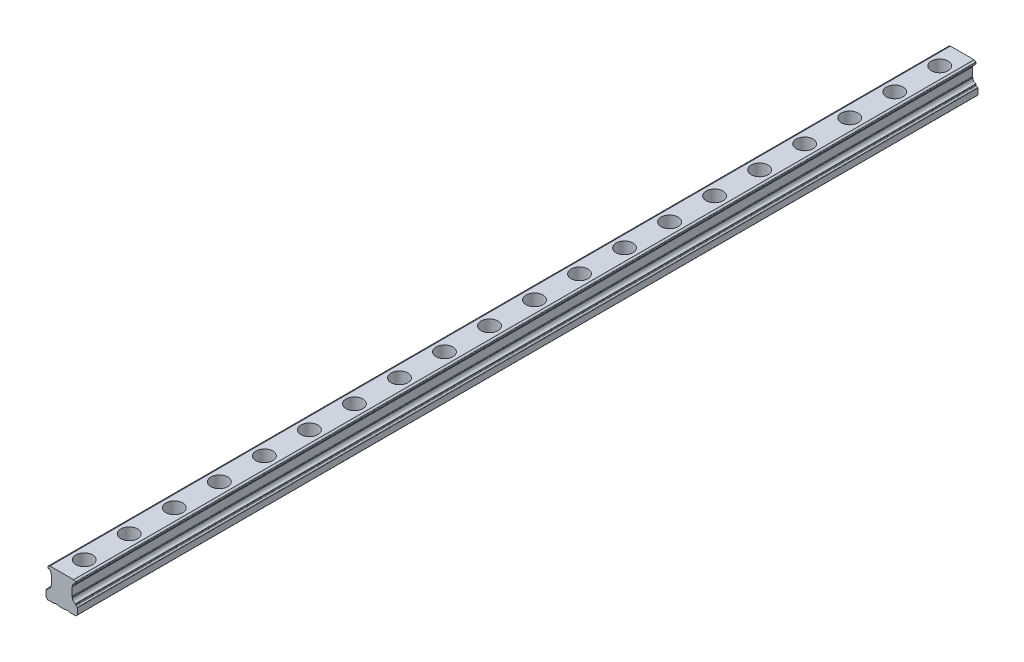
SolidWorks part; units mm, degrees
ref_plane "Ön Düzlem" through (0, 0, 0) normal (0, 0, 1) x (1, 0, 0)
ref_plane "Üst Düzlem" through (0, 0, 0) normal (0, 1, 0) x (1, 0, 0)
ref_plane "Sağ Düzlem" through (0, 0, 0) normal (1, 0, 0) x (0, 0, -1)
sketch "Çizim1" plane through (0, 0, 0) normal (0, 0, 1) x (1, 0, 0)
  line L0 (-8.9, 6.9858) -> (-8.9, -0.1858)
  line L1 (-9.0757, -0.6101) -> (-9.2828, -0.8172)
  line L2 (-12.2, -4.2749) -> (-12.2, -5.1311)
  line L3 (-12.5948, -5.695) -> (-13.7368, -6.1106)
  line L4 (-14, -6.4865) -> (-14, -11.7929)
  line L5 (-13.8828, -12.0757) -> (-12.5757, -13.3828)
  line L6 (-12.2929, -13.5) -> (-6.7271, -13.5)
  line L7 (-6.3736, -13.3536) -> (-6.1164, -13.0964)
  line L8 (-5.7629, -12.95) -> (-3.5771, -12.95)
  line L9 (-3.2236, -13.0964) -> (-2.9664, -13.3536)
  line L10 (-2.6129, -13.5) -> (2.6129, -13.5)
  line L11 (2.9664, -13.3536) -> (3.2236, -13.0964)
  line L12 (3.5771, -12.95) -> (5.7629, -12.95)
  line L13 (6.1164, -13.0964) -> (6.3736, -13.3536)
  line L14 (6.7271, -13.5) -> (12.2929, -13.5)
  line L15 (12.5757, -13.3828) -> (13.8828, -12.0757)
  line L16 (14, -11.7929) -> (14, -6.4865)
  line L17 (13.7368, -6.1106) -> (12.5948, -5.695)
  line L18 (12.2, -5.1311) -> (12.2, -4.2749)
  line L19 (9.2828, -0.8172) -> (9.0757, -0.6101)
  line L20 (8.9, -0.1858) -> (8.9, 6.9858)
  line L21 (9.0757, 7.4101) -> (9.2828, 7.6172)
  line L22 (12.3, 11.1757) -> (12.3, 12.2536)
  line L23 (12.1, 12.6) -> (10.634, 13.4464)
  line L24 (10.434, 13.5) -> (-10.434, 13.5)
  line L25 (-10.634, 13.4464) -> (-12.1, 12.6)
  line L26 (-12.3, 12.2536) -> (-12.3, 11.1757)
  line L27 (-9.2828, 7.6172) -> (-9.0757, 7.4101)
  arc A0 (-8.9, 6.9858) -> (-9.0757, 7.4101) centre (-9.5, 6.9858) ccw
  arc A1 (-9.0757, -0.6101) -> (-8.9, -0.1858) centre (-9.5, -0.1858) ccw
  arc A2 (-9.2828, -0.8172) -> (-9.4, -1.1) centre (-9, -1.1) ccw
  arc A3 (-12.1125, -4.1757) -> (-9.4, -1.1) centre (-12.5, -1.1) ccw
  arc A4 (-12.1125, -4.1757) -> (-12.2, -4.2749) centre (-12.1, -4.2749) ccw
  arc A5 (-12.5948, -5.695) -> (-12.2, -5.1311) centre (-12.8, -5.1311) ccw
  arc A6 (-13.7368, -6.1106) -> (-14, -6.4865) centre (-13.6, -6.4865) ccw
  arc A7 (-14, -11.7929) -> (-13.8828, -12.0757) centre (-13.6, -11.7929) ccw
  arc A8 (-12.5757, -13.3828) -> (-12.2929, -13.5) centre (-12.2929, -13.1) ccw
  arc A9 (-6.7271, -13.5) -> (-6.3736, -13.3536) centre (-6.7271, -13) ccw
  arc A10 (-5.7629, -12.95) -> (-6.1164, -13.0964) centre (-5.7629, -13.45) ccw
  arc A11 (-3.2236, -13.0964) -> (-3.5771, -12.95) centre (-3.5771, -13.45) ccw
  arc A12 (-2.9664, -13.3536) -> (-2.6129, -13.5) centre (-2.6129, -13) ccw
  arc A13 (2.6129, -13.5) -> (2.9664, -13.3536) centre (2.6129, -13) ccw
  arc A14 (3.5771, -12.95) -> (3.2236, -13.0964) centre (3.5771, -13.45) ccw
  arc A15 (6.1164, -13.0964) -> (5.7629, -12.95) centre (5.7629, -13.45) ccw
  arc A16 (6.3736, -13.3536) -> (6.7271, -13.5) centre (6.7271, -13) ccw
  arc A17 (12.2929, -13.5) -> (12.5757, -13.3828) centre (12.2929, -13.1) ccw
  arc A18 (13.8828, -12.0757) -> (14, -11.7929) centre (13.6, -11.7929) ccw
  arc A19 (14, -6.4865) -> (13.7368, -6.1106) centre (13.6, -6.4865) ccw
  arc A20 (12.2, -5.1311) -> (12.5948, -5.695) centre (12.8, -5.1311) ccw
  arc A21 (12.2, -4.2749) -> (12.1125, -4.1757) centre (12.1, -4.2749) ccw
  arc A22 (9.4, -1.1) -> (12.1125, -4.1757) centre (12.5, -1.1) ccw
  arc A23 (9.4, -1.1) -> (9.2828, -0.8172) centre (9, -1.1) ccw
  arc A24 (8.9, -0.1858) -> (9.0757, -0.6101) centre (9.5, -0.1858) ccw
  arc A25 (9.0757, 7.4101) -> (8.9, 6.9858) centre (9.5, 6.9858) ccw
  arc A26 (9.2828, 7.6172) -> (9.4, 7.9) centre (9, 7.9) ccw
  arc A27 (12.1242, 10.9771) -> (9.4, 7.9) centre (12.5, 7.9) ccw
  arc A28 (12.1242, 10.9771) -> (12.3, 11.1757) centre (12.1, 11.1757) ccw
  arc A29 (12.3, 12.2536) -> (12.1, 12.6) centre (11.9, 12.2536) ccw
  arc A30 (10.634, 13.4464) -> (10.434, 13.5) centre (10.434, 13.1) ccw
  arc A31 (-10.434, 13.5) -> (-10.634, 13.4464) centre (-10.434, 13.1) ccw
  arc A32 (-12.1, 12.6) -> (-12.3, 12.2536) centre (-11.9, 12.2536) ccw
  arc A33 (-12.3, 11.1757) -> (-12.1242, 10.9771) centre (-12.1, 11.1757) ccw
  arc A34 (-9.4, 7.9) -> (-12.1242, 10.9771) centre (-12.5, 7.9) ccw
  arc A35 (-9.4, 7.9) -> (-9.2828, 7.6172) centre (-9, 7.9) ccw
extrude "Yükseklik-Ekstrüzyon1" add sketch "Çizim1" along normal mid plane 800
hole_wizard "M8 Altıgen Alyan Başlı Kör Vida İçin Havşa1" positions "3B Çizim1" profile "Çizim2" counterbore size "M8" standard "DIN"
sketch3d "3B Çizim1"
  line L0 (0, 13.5, 400) -> (0, 13.5, 380) construction
  line L1 (10.434, 13.5, 400) -> (-10.434, 13.5, 400) construction
  point P0 (0, 13.5, 380)
  dimension "D1" = 20
sketch "Çizim2" plane through (0, 13.5, 380) normal (1, 0, 0) x (0, 0, 1)
  line L0 (0, 0) -> (0, 33.9539)
  line L1 (0, 33.9539) -> (4.5, 31.25)
  line L2 (4.5, 31.25) -> (4.5, 13.6)
  line L3 (4.5, 13.6) -> (7.5, 13.6)
  line L4 (7.5, 13.6) -> (7.5, 0)
  line L5 (7.5, 0) -> (0, 0)
  line L10 (0, 33.9539) -> (-4.5, 31.25) construction
  line L11 (0, -6.35) -> (0, 107.95) construction
  dimension "Hole Dia." = 9
  dimension "Hole Depth" = 31.25
  dimension "C'Bore Dia." = 15
  dimension "C'Bore Depth" = 13.6
  dimension "Drill Angle" = 118
pattern_linear "LÇoğaltma1" count 20 spacing 40 along (0, 0, -1) of "M8 Altıgen Alyan Başlı Kör Vida İçin Havşa1"
